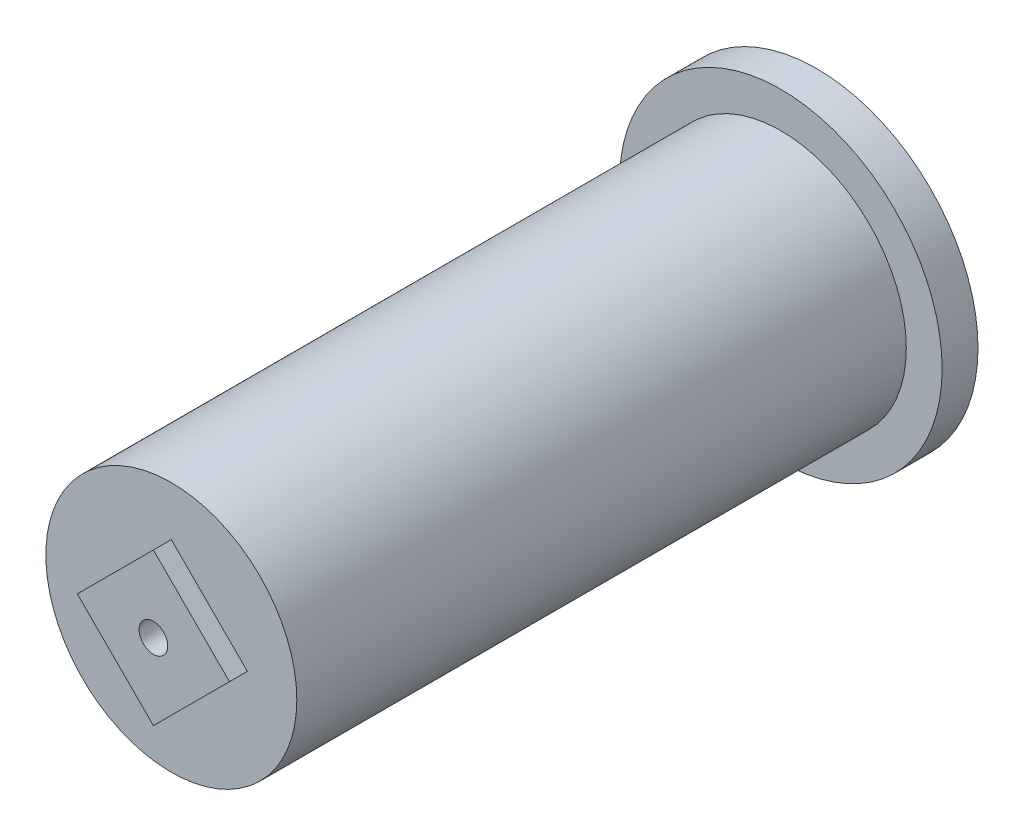
SolidWorks part; units mm, degrees
ref_plane "Спереди" through (0, 0, 0) normal (0, 0, 1) x (1, 0, 0)
ref_plane "Сверху" through (0, 0, 0) normal (0, 1, 0) x (1, 0, 0)
ref_plane "Справа" through (0, 0, 0) normal (1, 0, 0) x (0, 0, -1)
sketch "Эскиз1" plane through (0, 0, 0) normal (0, 0, 1) x (1, 0, 0)
  circle A0 centre (0, 0) radius 22.5
  dimension "D1" = 45
extrude "Бобышка-Вытянуть1" add sketch "Эскиз1" along normal blind 5
sketch "Эскиз2" plane through (0, 0, 5) normal (0, 0, 1) x (1, 0, 0)
  circle A0 centre (0, 0) radius 17.5
  dimension "D1" = 35
extrude "Бобышка-Вытянуть2" add sketch "Эскиз2" along normal blind 85
sketch "Эскиз3" plane through (0, 0, 90) normal (0, 0, 1) x (1, 0, 0)
  line L1 (10.6066, 0) -> (0, 10.6066)
  line L2 (0, 10.6066) -> (-10.6066, 0)
  line L3 (-10.6066, 0) -> (0, -10.6066)
  line L4 (0, -10.6066) -> (10.6066, 0)
  circle A0 centre (0, 0) radius 7.5 construction
  dimension "D1" = 15
extrude "Бобышка-Вытянуть3" add sketch "Эскиз3" along normal blind 2.5
sketch "Эскиз4" plane through (0, 0, 92.5) normal (0, 0, 1) x (1, 0, 0)
  circle A0 centre (0, 0) radius 2
  dimension "D1" = 4
extrude "Вырез-Вытянуть1" cut sketch "Эскиз4" against normal blind 50 contours A0
